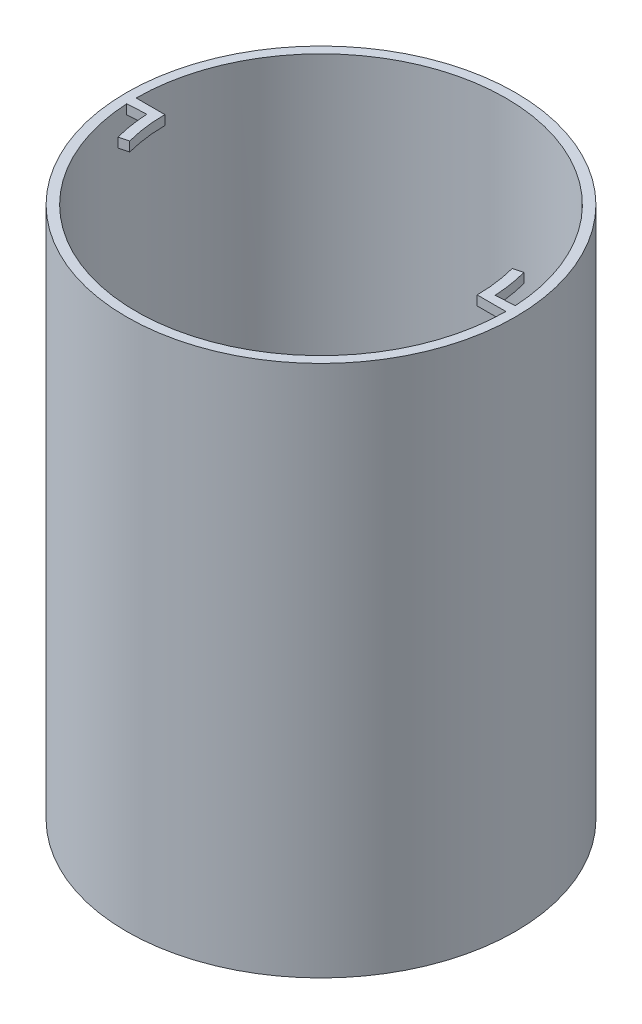
SolidWorks part; units mm, degrees
ref_plane "Front Plane" through (0, 0, 0) normal (0, 0, 1) x (1, 0, 0)
ref_plane "Top Plane" through (0, 0, 0) normal (0, 1, 0) x (1, 0, 0)
ref_plane "Right Plane" through (0, 0, 0) normal (1, 0, 0) x (0, 0, -1)
sketch "Sketch1" plane through (0, 0, 0) normal (0, 0, 1) x (1, 0, 0)
  line L10 (0, 0) -> (0, 250) construction
  line L11 (61, 167) -> (58, 167)
  line L15 (58, 167) -> (58, 0)
  line L16 (58, 0) -> (61, 0)
  line L22 (61, 0) -> (61, 167)
  dimension "D1" = 3
  dimension "D2" = 61
  dimension "D3" = 167
revolve "Revolve1" add sketch "Sketch1" angle 360 about L10
sketch "Sketch2" plane through (0, 0, 0) normal (0, 0, 1) x (1, 0, 0)
  line L0 (61, 167) -> (52, 167)
  line L1 (61, 167) -> (-61, 167) construction
  line L2 (52, 167) -> (52, 164)
  line L3 (52, 164) -> (58, 164)
  line L4 (58, 164) -> (58, 167)
  line L5 (0, 0) -> (0, 167) construction
  line L6 (-58, 164) -> (-58, 167)
  line L7 (-61, 167) -> (-52, 167)
  line L8 (-52, 167) -> (-52, 164)
  line L9 (-52, 164) -> (-58, 164)
  dimension "D1" = 9
  dimension "D2" = 3
  dimension "D3" = 6
revolve "Revolve2" add sketch "Sketch2" angle 3 about L5
sketch "Sketch3" plane through (0, 0, 0) normal (0, 0, 1) x (1, 0, 0)
  line L0 (61, 167) -> (49, 167)
  line L1 (58, 167) -> (-57.9205, 167) construction
  line L2 (49, 167) -> (49, 164)
  line L3 (49, 164) -> (52, 164)
  line L4 (52, 164) -> (52, 167)
  line L5 (0, 0) -> (0, 167) construction
  line L6 (61, 167) -> (-61, 167) construction
  line L7 (-61, 167) -> (-49, 167)
  line L8 (-52, 164) -> (-52, 167)
  line L9 (-49, 167) -> (-49, 164)
  line L10 (-49, 164) -> (-52, 164)
  dimension "D1" = 12
  dimension "D2" = 3
  dimension "D3" = 3
revolve "Revolve3" add sketch "Sketch3" angle 15 about L5
